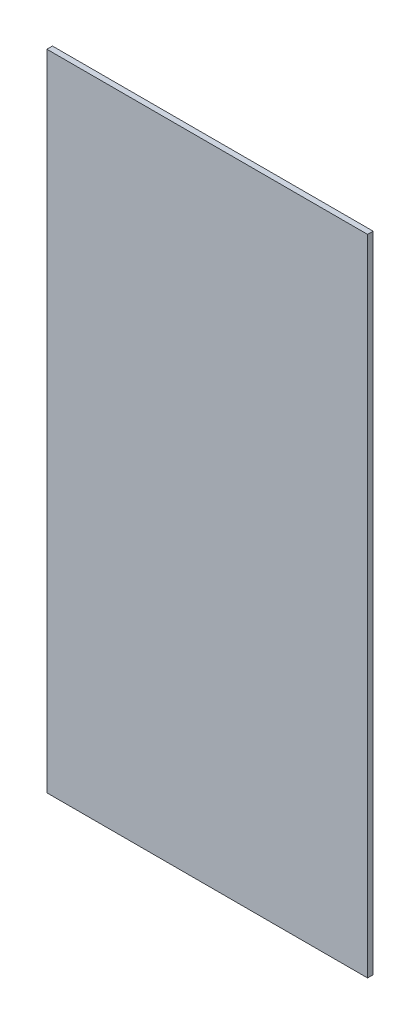
SolidWorks part; units mm, degrees
ref_plane "Plan de face" through (0, 0, 0) normal (0, 0, 1) x (1, 0, 0)
ref_plane "Plan de dessus" through (0, 0, 0) normal (0, 1, 0) x (1, 0, 0)
ref_plane "Plan de droite" through (0, 0, 0) normal (1, 0, 0) x (0, 0, -1)
sketch "Esquisse1" plane through (0, 0, 0) normal (0, 0, 1) x (1, 0, 0)
  line L1 (-187.5, -376.5) -> (187.5, -376.5)
  line L2 (-187.5, -376.5) -> (-187.5, 376.5)
  line L3 (-187.5, 376.5) -> (187.5, 376.5)
  line L4 (187.5, -376.5) -> (187.5, 376.5)
  line L5 (-187.5, -376.5) -> (187.5, 376.5) construction
  line L6 (-187.5, 376.5) -> (187.5, -376.5) construction
  point P0 (0, 0)
  dimension "D1" = 753
  dimension "D2" = 375
extrude "Boss.-Extru.1" add sketch "Esquisse1" along normal blind 6.5
